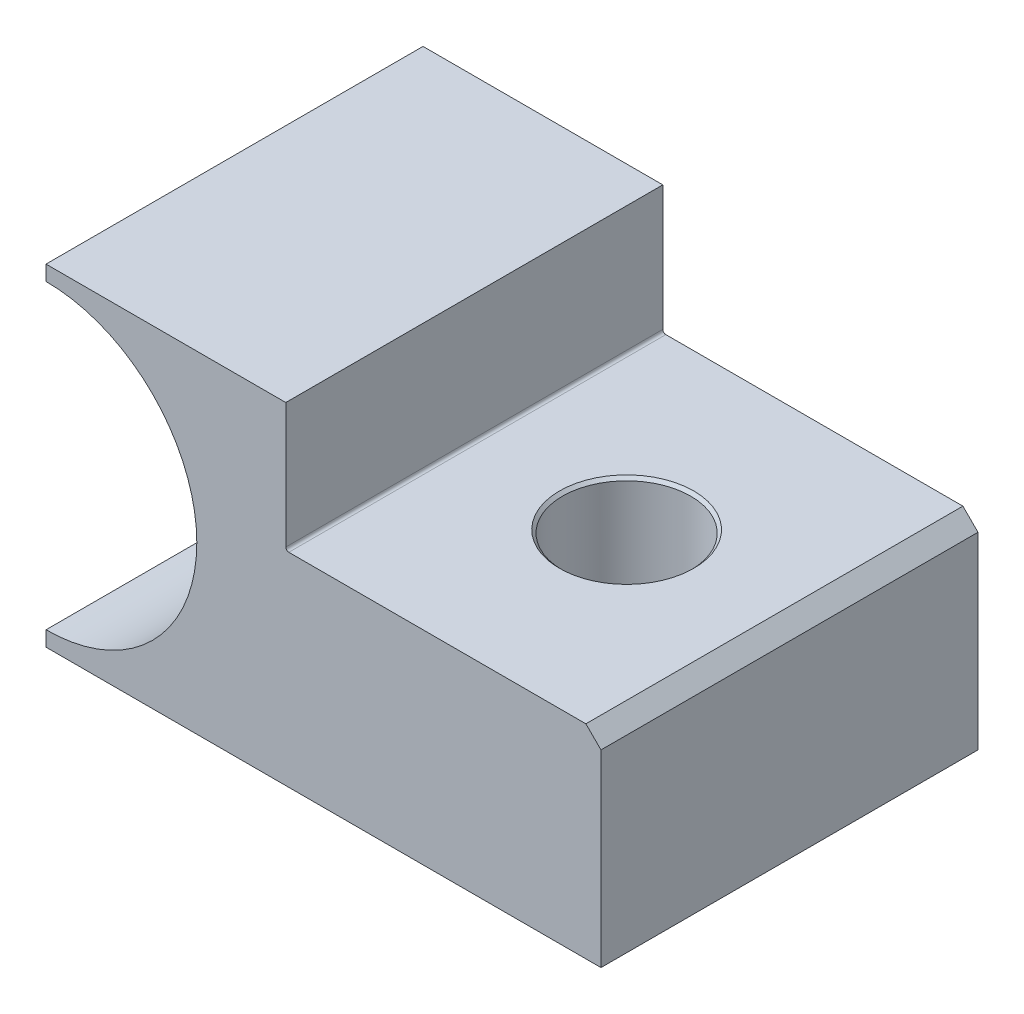
SolidWorks part; units mm, degrees
material "AISI Type A2 Tool Steel Custom"
ref_plane "Front Plane" through (0, 0, 0) normal (0, 0, 1) x (1, 0, 0)
ref_plane "Top Plane" through (0, 0, 0) normal (0, 1, 0) x (1, 0, 0)
ref_plane "Right Plane" through (0, 0, 0) normal (1, 0, 0) x (0, 0, -1)
sketch "Sketch1" plane through (0, 0, 0) normal (0, 0, 1) x (1, 0, 0)
  line L4 (46.736, 0) -> (46.736, 17.145)
  line L6 (20.193, 27.94) -> (20.193, 17.145)
  line L7 (20.193, 17.145) -> (46.736, 17.145)
  line L9 (0, 26.67) -> (0, 27.94)
  line L10 (0, 27.94) -> (20.193, 27.94)
  line L11 (0, 1.27) -> (0, 0)
  line L12 (0, 0) -> (46.736, 0)
  arc A1 (0, 1.27) -> (0, 26.67) centre (0, 13.97) ccw
  dimension "D2" = 25.4
  dimension "D1" = 10.795
  dimension "D3" = 17.145
  dimension "D4" = 46.736
  dimension "D5" = 26.543
  dimension "D6" = 1.27
  dimension "D7" = 1.27
extrude "Boss-Extrude1" add sketch "Sketch1" along normal blind 31.75
sketch "Sketch5" plane through (0, 17.145, 0) normal (0, 1, 0) x (1, 0, 0)
  line L2 (0, -31.75) -> (0, 0) construction
  point P0 (33.02, -15.875)
  point P12 (0, -15.875)
  dimension "D1" = 33.02
hole_wizard "X (0.397) Diameter Hole1" positions "Sketch5" profile "Sketch4" hole size "X" standard "ANSI Inch" end condition through all
sketch "Sketch4" plane through (33.02, 17.145, 15.875) normal (1, 0, 0) x (0, 0, 1)
  line L0 (0, 0) -> (0, 17.145)
  line L1 (0, 17.145) -> (5.3975, 17.145)
  line L2 (5.3975, 17.145) -> (5.3975, 0)
  line L5 (5.3975, 0) -> (0, 0)
  line L11 (0, -6.35) -> (0, 107.95) construction
  dimension "Thru Hole Dia." = 10.795
  dimension "Thru Hole Depth" = 17.145
chamfer "Chamfer1" distance 1.27 angle 45 1 edges at (46.736, 17.145, 15.875)
chamfer "Chamfer2" distance 0.254 angle 45 1 edges at (33.02, 17.145, 21.2725)
fillet "Fillet1" radius 0.254 1 edges at (20.193, 17.145, 15.875)
